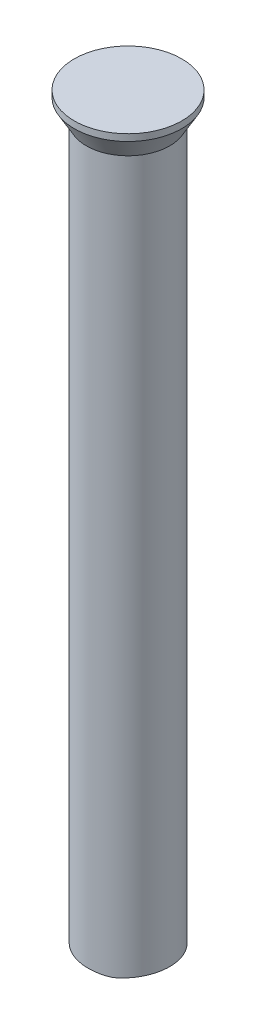
SolidWorks part; units mm, degrees
material "M2 HSS"
ref_plane "Front Plane" through (0, 0, 0) normal (0, 0, 1) x (1, 0, 0)
ref_plane "Top Plane" through (0, 0, 0) normal (0, 1, 0) x (1, 0, 0)
ref_plane "Right Plane" through (0, 0, 0) normal (1, 0, 0) x (0, 0, -1)
sketch "Sketch1" plane through (0, 0, 0) normal (0, 0, 1) x (1, 0, 0)
  line L0 (0, 0) -> (4, 0)
  line L1 (4, 0) -> (4, -0.5)
  line L2 (4, -0.5) -> (3.1, -2.0588)
  line L3 (3.1, -2.0588) -> (3.1, -55.2)
  line L4 (3.1, -55.2) -> (0, -55.2)
  line L5 (0, -55.2) -> (0, 0)
  line L6 (0, -60.2) -> (0, 5) construction
  dimension "D1" = 5
  dimension "D2" = 5
  dimension "D3" = 0.5
  dimension "D4" = 30
  dimension "D5" = 6.2
  dimension "D6" = 8
  dimension "D7" = 55.2
revolve "Revolve1" add sketch "Sketch1" angle 360 about L6
sketch "Sketch2" plane through (0, 0, 0) normal (0, 0, 1) x (1, 0, 0)
  line L0 (0, -55.2) -> (3.1, -55.2)
  line L1 (-3.1, -55.2) -> (3.1, -55.2) construction
  line L2 (3.1, -55.2) -> (3.1, -54.9288)
  line L3 (3.1, -55.2) -> (3.1, -2.0588) construction
  line L4 (3.1, -54.9288) -> (0, -55.2)
  dimension "D1" = 5
  dimension "D2" = 0.2712
extrude "Cut-Extrude1" cut sketch "Sketch2" against normal through all both and the other way through all
pattern_circular "CirPattern1" count 3 over 360 about axis through (0, 0, 0) along (0, 1, 0) of "Cut-Extrude1"
